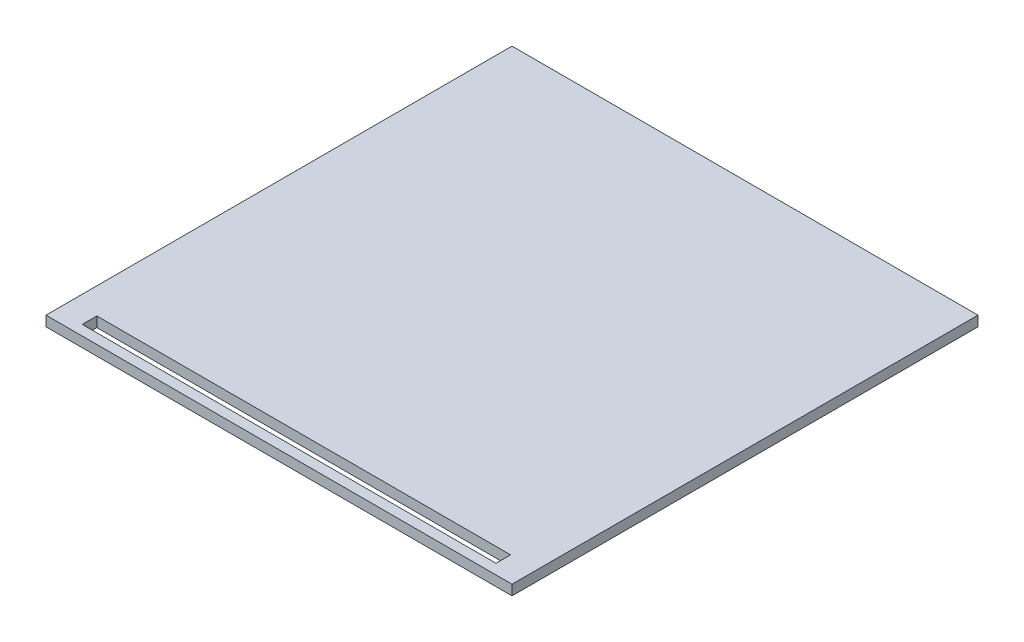
SolidWorks part; units mm, degrees
other "Marquage1"
sketch "Esquisse9" plane through (-102, 305, -109) normal (-0.0966, 0.0752, -0.9925) x (-0.9782, -0.1912, 0.0807)
ref_plane "Front Plane" through (0, 0, 0) normal (0, 0, 1) x (1, 0, 0)
ref_plane "Top Plane" through (0, 0, 0) normal (0, 1, 0) x (1, 0, 0)
ref_plane "Right Plane" through (0, 0, 0) normal (1, 0, 0) x (0, 0, -1)
sketch "Esquisse3" plane through (0, 0, 0) normal (0, 1, 0) x (1, 0, 0)
  line L0 (-115, 115) -> (115, 115)
  line L1 (-115, -115) -> (115, -115)
  line L2 (-115, -115) -> (-115, 115)
  line L4 (115, -115) -> (115, 115)
  line L5 (-115, -115) -> (115, 115) construction
  line L6 (-115, 115) -> (115, -115) construction
  point P0 (0, 0)
  dimension "D4" = 230
extrude "Boss.-Extru.1" add sketch "Esquisse3" along normal blind 5
sketch "Esquisse10" plane through (0, 5, 0) normal (0, 1, 0) x (1, 0, 0)
  line L0 (-115, -115) -> (115, -115) construction
  line L1 (102.1, -110) -> (-102.1, -110)
  line L2 (102.1, -110) -> (102.1, -102.8)
  line L3 (102.1, -102.8) -> (-102.1, -102.8)
  line L4 (-102.1, -110) -> (-102.1, -102.8)
  line L5 (0, -115) -> (0, 115) construction
  line L6 (115, 115) -> (-115, 115) construction
  dimension "D1" = 5
  dimension "D2" = 7.2
  dimension "D3" = 204.2
extrude "Enlèv. mat.-Extru.1" cut sketch "Esquisse10" against normal through all
